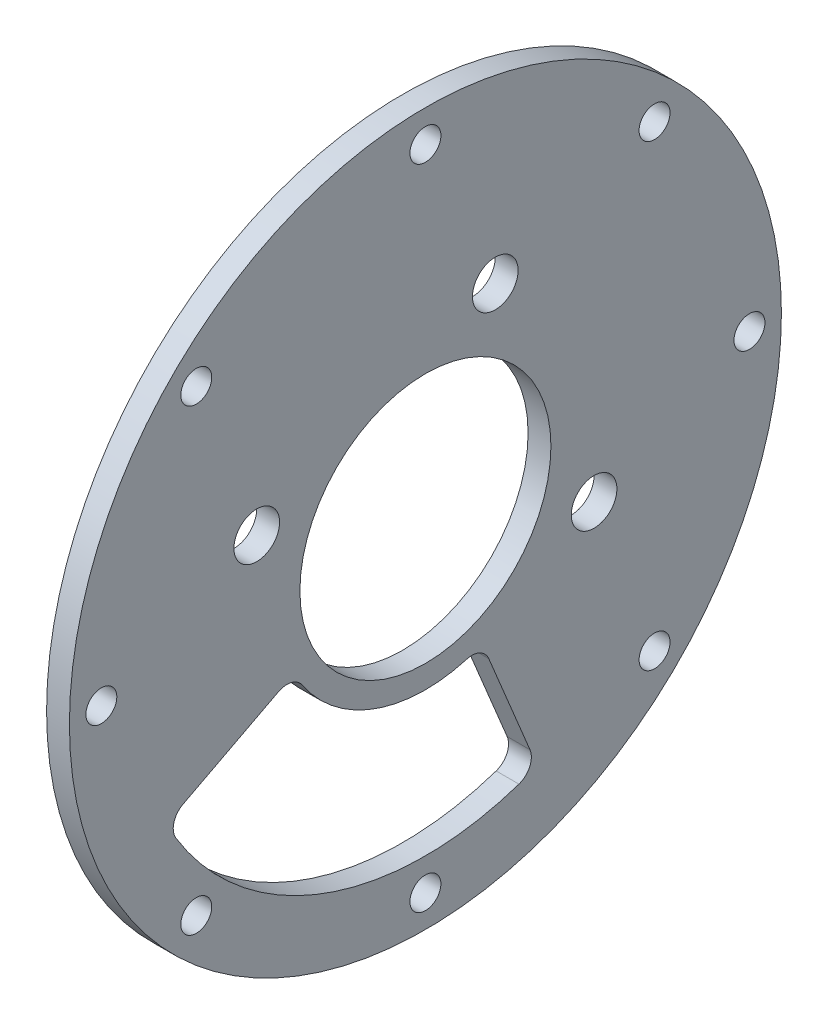
SolidWorks part; units mm, degrees
ref_plane "Front Plane" through (0, 0, 0) normal (0, 0, 1) x (1, 0, 0)
ref_plane "Top Plane" through (0, 0, 0) normal (0, 1, 0) x (1, 0, 0)
ref_plane "Right Plane" through (0, 0, 0) normal (1, 0, 0) x (0, 0, -1)
sketch "Sketch1" plane through (0, 0, 0) normal (1, 0, 0) x (0, 0, -1)
  line L0 (9.7202, 23.4665) -> (0, 0) construction
  circle A0 centre (0, 0) radius 49.53
  circle A1 centre (0, 45.085) radius 2.1527
  circle A2 centre (31.8799, 31.8799) radius 2.1527
  circle A3 centre (45.085, 0) radius 2.1527
  circle A4 centre (31.8799, -31.8799) radius 2.1527
  circle A5 centre (0, -45.085) radius 2.1527
  circle A6 centre (-31.8799, -31.8799) radius 2.1527
  circle A7 centre (-45.085, 0) radius 2.1527
  circle A8 centre (-31.8799, 31.8799) radius 2.1527
  circle A9 centre (0, 0) radius 17.4625
  circle A10 centre (9.7202, 23.4665) radius 3.175
  circle A11 centre (23.4665, -9.7202) radius 3.175
  circle A12 centre (-9.7202, -23.4665) radius 3.175
  circle A13 centre (-23.4665, 9.7202) radius 3.175
  dimension "D1" = 99.06
  dimension "D2" = 4.3053
  dimension "D4" = 34.925
  dimension "D5" = 6.35
  dimension "D3" = 45.085
  dimension "D6" = 25.4
extrude "Boss-Extrude1" add sketch "Sketch1" along normal blind 3.175
sketch "Sketch2" plane through (3.175, 0, 0) normal (1, 0, 0) x (0, 0, -1)
  line L0 (-20.4349, -10.6377) -> (-33.7199, -17.5535)
  line L1 (8.8162, -21.2842) -> (14.5478, -35.1215)
  line L2 (0, 0) -> (-9.7202, -23.4665) construction
  circle A2 centre (-9.7202, -23.4665) radius 3.175 construction
  arc A3 (-17.1511, -11.478) -> (5.7606, -19.8172) centre (0, 0) ccw
  arc A4 (13.0146, -38.4998) -> (-34.7169, -21.1269) centre (0, 0) cw
  circle A5 centre (0, 0) radius 49.53 construction
  arc A6 (14.5478, -35.1215) -> (13.0146, -38.4998) centre (12.2011, -36.0935) cw
  arc A7 (-34.7169, -21.1269) -> (-33.7199, -17.5535) centre (-32.5471, -19.8065) cw
  circle A8 centre (0, 0) radius 17.4625 construction
  arc A9 (5.7606, -19.8172) -> (8.8162, -21.2842) centre (6.4696, -22.2563) cw
  arc A10 (-20.4349, -10.6377) -> (-17.1511, -11.478) centre (-19.262, -12.8907) cw
  dimension "D3" = 8.89
  dimension "D4" = 2.54
  dimension "D5" = 3.175
  dimension "D6" = 2.54
  dimension "D1" = 85
  dimension "D2" = 40
extrude "Cut-Extrude1" cut sketch "Sketch2" against normal through all
